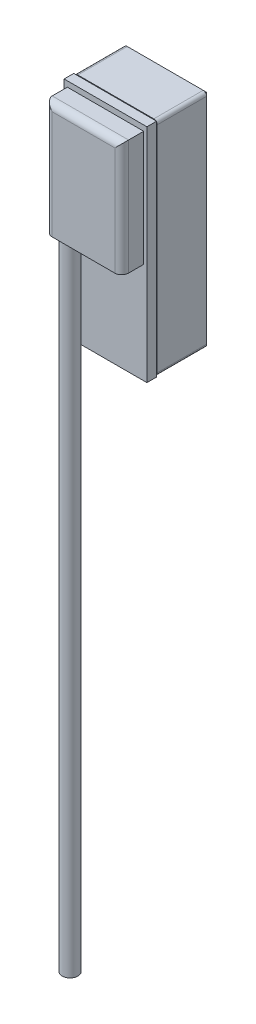
SolidWorks part; units mm, degrees
ref_plane "Спереди" through (0, 0, 0) normal (0, 0, 1) x (1, 0, 0)
ref_plane "Сверху" through (0, 0, 0) normal (0, 1, 0) x (1, 0, 0)
ref_plane "Справа" through (0, 0, 0) normal (1, 0, 0) x (0, 0, -1)
sketch "Эскиз1" plane through (0, 0, 0) normal (0, 0, 1) x (1, 0, 0)
  line L1 (-3.01, -8.055) -> (3.01, -8.055)
  line L2 (-3.01, -8.055) -> (-3.01, 8.055)
  line L3 (-3.01, 8.055) -> (3.01, 8.055)
  line L4 (3.01, -8.055) -> (3.01, 8.055)
  line L5 (-3.01, -8.055) -> (3.01, 8.055) construction
  line L6 (-3.01, 8.055) -> (3.01, -8.055) construction
  point P0 (0, 0)
  dimension "D1" = 6.02
  dimension "D2" = 16.11
extrude "Бобышка-Вытянуть1" add sketch "Эскиз1" along normal blind 3.84
sketch "Эскиз2" plane through (0, 0, 0) normal (0, 0, -1) x (-1, 0, 0)
  line L0 (-3.01, -8.055) -> (-3.01, 8.055) construction
  line L1 (-3.01, 8.055) -> (3.01, 8.055) construction
  circle A0 centre (-0.87, 0.795) radius 0.725
  dimension "D1" = 1.45
  dimension "D2" = 2.14
  dimension "D3" = 7.26
extrude "Бобышка-Вытянуть2" add sketch "Эскиз2" along normal blind 0.2
ref_plane "Плоскость1" through (0, 0, 3.89) normal (0, 0, 1) x (1, 0, 0)
sketch "Эскиз3" plane through (0, 0, 3.89) normal (0, 0, 1) x (1, 0, 0)
  line L1 (-3.01, -8.055) -> (3.01, -8.055)
  line L2 (-3.01, -8.055) -> (-3.01, 8.055)
  line L3 (-3.01, 8.055) -> (3.01, 8.055)
  line L4 (3.01, -8.055) -> (3.01, 8.055)
  line L5 (-3.01, -8.055) -> (3.01, 8.055) construction
  line L6 (-3.01, 8.055) -> (3.01, -8.055) construction
  point P0 (0, 0)
extrude "Бобышка-Вытянуть3" add sketch "Эскиз3" along normal blind 0.7 separate body
sketch "Эскиз4" plane through (0, 0, 4.59) normal (0, 0, 1) x (1, 0, 0)
  line L0 (3.01, 8.055) -> (-3.01, 8.055) construction
  line L1 (-2.775, -0.725) -> (2.775, -0.725)
  line L2 (-2.775, -0.725) -> (-2.775, 7.655)
  line L3 (-2.775, 7.655) -> (2.775, 7.655)
  line L4 (2.775, -0.725) -> (2.775, 7.655)
  line L5 (-2.775, -0.725) -> (2.775, 7.655) construction
  line L6 (-2.775, 7.655) -> (2.775, -0.725) construction
  point P0 (0, 3.465)
  point P5 (0, 0)
  point P6 (0, 0)
  point P7 (0, 3.2771)
  dimension "D1" = 8.38
  dimension "D2" = 5.55
  dimension "D3" = 0.4
extrude "Бобышка-Вытянуть4" add sketch "Эскиз4" along normal blind 1.6
sketch "Эскиз5" plane through (0, -0.725, 0) normal (0, -1, 0) x (1, 0, 0)
  line L0 (-2.775, 5.39) -> (2.775, 5.39) construction
  line L1 (-2.775, 6.19) -> (-2.775, 4.59) construction
  line L2 (2.775, 6.19) -> (2.775, 4.59) construction
  circle A0 centre (-1.775, 5.39) radius 0.57
  point P8 (0, 0)
  dimension "D1" = 1.14
  dimension "D2" = 1
extrude "Бобышка-Вытянуть5" add sketch "Эскиз5" along normal blind 46.4
fillet "Скругление1" radius 0.5 3 edges at (-2.775, 3.465, 6.19) (0, 7.655, 6.19) (2.775, 3.465, 6.19)
fillet "Скругление2" radius 0.25 4 edges at (-3.01, -8.055, 1.92) (3.01, -8.055, 1.92) (3.01, 8.055, 1.92) (-3.01, 8.055, 1.92)
chamfer "Фаска1" distance 0.25 angle 45 8 edges at (3.01, 0, 0) (2.9368, 7.9818, 0) (2.9368, -7.9818, 0) (0, 8.055, 0) (0, -8.055, 0) (-2.9368, 7.9818, 0) (-2.9368, -7.9818, 0) (-3.01, 0, 0)
